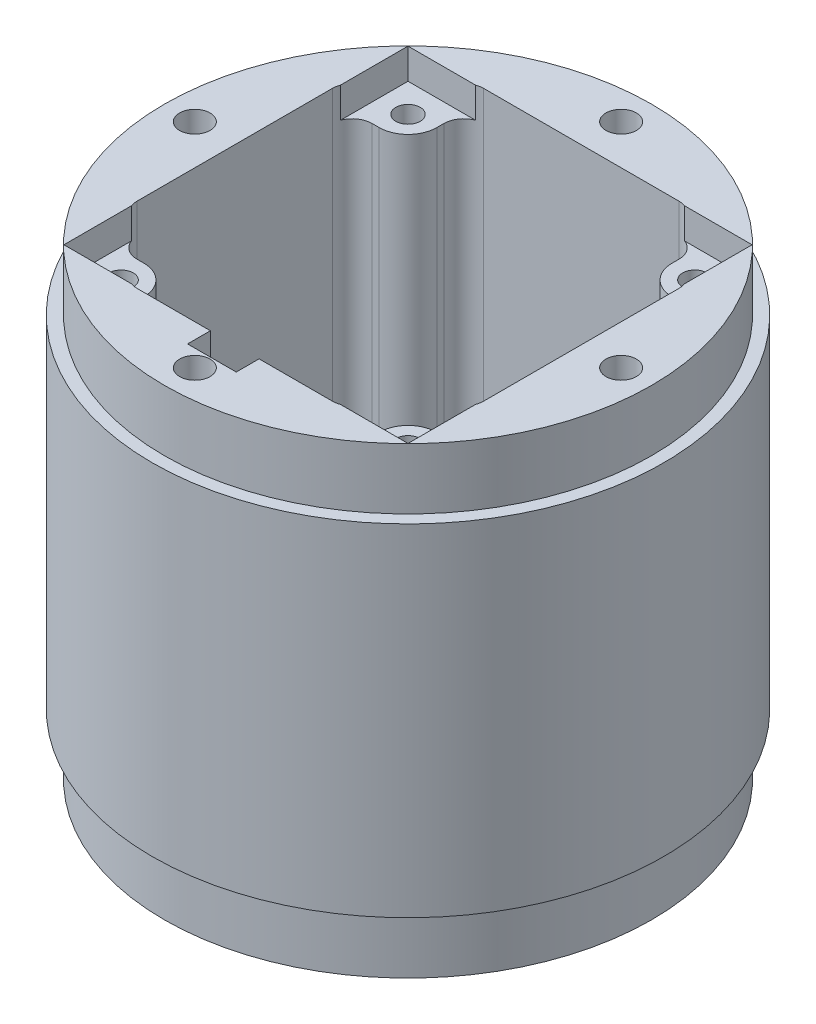
SolidWorks part; units mm, degrees
ref_plane "Front Plane" through (0, 0, 0) normal (0, 0, 1) x (1, 0, 0)
ref_plane "Top Plane" through (0, 0, 0) normal (0, 1, 0) x (1, 0, 0)
ref_plane "Right Plane" through (0, 0, 0) normal (1, 0, 0) x (0, 0, -1)
sketch "Sketch2" plane through (0, 0, 0) normal (0, 1, 0) x (1, 0, 0)
  line L0 (-16.05, 28.45) -> (16.05, 28.45)
  line L5 (19.3, 25.2) -> (19.3, 24.05)
  line L7 (-16.05, 28.2) -> (16.05, 28.2) construction
  line L8 (-28.2, 16.05) -> (-28.2, -16.05)
  line L9 (-16.05, -28.2) -> (16.05, -28.2)
  line L10 (28.2, 16.05) -> (28.2, -16.05)
  line L11 (25.2, 19.3) -> (24.05, 19.3)
  line L12 (28.45, 16.05) -> (28.45, -16.05)
  line L15 (-25.2, 19.05) -> (-24.05, 19.05)
  line L16 (-19.05, 25.2) -> (-19.05, 24.05)
  line L19 (25.2, 19.05) -> (24.05, 19.05)
  line L20 (19.05, 25.2) -> (19.05, 24.05)
  line L21 (-24.05, -19.05) -> (-25.2, -19.05)
  line L22 (-19.05, -24.05) -> (-19.05, -25.2)
  line L25 (24.05, -19.05) -> (25.2, -19.05)
  line L26 (19.05, -24.05) -> (19.05, -25.2)
  line L27 (24.05, -19.3) -> (25.2, -19.3)
  line L28 (19.3, -24.05) -> (19.3, -25.2)
  line L29 (-16.05, -28.45) -> (16.05, -28.45)
  line L30 (-19.3, -24.05) -> (-19.3, -25.2)
  line L31 (-24.05, -19.3) -> (-25.2, -19.3)
  line L32 (-28.45, 16.05) -> (-28.45, -16.05)
  line L33 (-25.2, 19.3) -> (-24.05, 19.3)
  line L34 (-19.3, 25.2) -> (-19.3, 24.05)
  circle A0 centre (0, 0) radius 40
  arc A1 (24.05, 19.05) -> (19.05, 24.05) centre (24.05, 24.05) cw
  arc A2 (-24.05, 19.05) -> (-19.05, 24.05) centre (-24.05, 24.05) ccw
  arc A3 (-24.05, -19.05) -> (-19.05, -24.05) centre (-24.05, -24.05) cw
  arc A4 (19.05, -24.05) -> (24.05, -19.05) centre (24.05, -24.05) cw
  arc A5 (-28.2, 16.05) -> (-25.2, 19.05) centre (-25.2, 16.05) cw
  arc A6 (-28.2, -16.05) -> (-25.2, -19.05) centre (-25.2, -16.05) ccw
  arc A7 (-16.05, -28.2) -> (-19.05, -25.2) centre (-16.05, -25.2) cw
  arc A8 (16.05, -28.2) -> (19.05, -25.2) centre (16.05, -25.2) ccw
  arc A9 (25.2, -19.05) -> (28.2, -16.05) centre (25.2, -16.05) ccw
  arc A10 (28.2, 16.05) -> (25.2, 19.05) centre (25.2, 16.05) ccw
  arc A11 (16.05, 28.2) -> (19.05, 25.2) centre (16.05, 25.2) cw
  arc A12 (-19.05, 25.2) -> (-16.05, 28.2) centre (-16.05, 25.2) cw
  arc A13 (16.05, 28.45) -> (19.3, 25.2) centre (16.05, 25.2) cw
  arc A14 (24.05, 19.3) -> (19.3, 24.05) centre (24.05, 24.05) cw
  arc A15 (28.45, 16.05) -> (25.2, 19.3) centre (25.2, 16.05) ccw
  arc A16 (25.2, -19.3) -> (28.45, -16.05) centre (25.2, -16.05) ccw
  arc A17 (19.3, -24.05) -> (24.05, -19.3) centre (24.05, -24.05) cw
  arc A18 (16.05, -28.45) -> (19.3, -25.2) centre (16.05, -25.2) ccw
  arc A19 (-16.05, -28.45) -> (-19.3, -25.2) centre (-16.05, -25.2) cw
  arc A20 (-24.05, -19.3) -> (-19.3, -24.05) centre (-24.05, -24.05) cw
  arc A21 (-28.45, -16.05) -> (-25.2, -19.3) centre (-25.2, -16.05) ccw
  arc A22 (-28.45, 16.05) -> (-25.2, 19.3) centre (-25.2, 16.05) cw
  arc A23 (-24.05, 19.3) -> (-19.3, 24.05) centre (-24.05, 24.05) ccw
  arc A24 (-19.3, 25.2) -> (-16.05, 28.45) centre (-16.05, 25.2) cw
  point P0 (0, 0)
  point P6 (0, 0)
  point P11 (19.05, 19.05)
  point P24 (-19.05, -19.05)
  point P27 (19.05, -19.05)
  point P40 (28.2, 19.05)
  point P43 (19.05, 28.2)
  point P46 (-19.05, 28.2)
  dimension "D7" = 80
  dimension "D8" = 5
  dimension "D9" = 3
  dimension "D1" = 38.1
  dimension "D2" = 38.1
  dimension "D3" = 9.15
  dimension "D4" = 38.1
  dimension "D5" = 9.15
  dimension "D6" = 28.2
  dimension "D10" = 0.25
extrude "Boss-Extrude1" add sketch "Sketch2" along normal blind 76 contours A0 L34 A24 L0 A13 L5 A14 L11 A15 L12 A16 L27 A17 L28 A18 L29 A19 L30 A20 L31 A21 L32 A22 L33 A23
sketch "Sketch3" plane through (0, 0, 28.2) normal (0, 0, -1) x (-1, 0, 0)
  line L0 (16.05, 0) -> (-16.05, 0) construction
  line L1 (-4, 76) -> (4, 76)
  line L2 (-4, 76) -> (-4, 0)
  line L3 (-4, 0) -> (4, 0)
  line L4 (4, 76) -> (4, 0)
  point P6 (0, 0)
  dimension "D1" = 8
  dimension "D2" = 76
extrude "Cut-Extrude1" cut sketch "Sketch3" against normal blind 4
ref_plane "Plane1" through (0, 38, 0) normal (0, 1, 0) x (1, 0, 0)
sketch "Sketch4" plane through (0, 38, 0) normal (0, 1, 0) x (1, 0, 0)
  circle A0 centre (0, 0) radius 42
  circle A1 centre (0, 0) radius 40
  dimension "D1" = 84
extrude "Boss-Extrude3" add sketch "Sketch4" along normal mid plane 56
sketch "Sketch5" plane through (0, 76, 0) normal (0, 1, 0) x (1, 0, 0)
  line L1 (-28.25, 28.25) -> (28.25, 28.25)
  line L2 (-28.25, 28.25) -> (-28.25, -28.25)
  line L3 (-28.25, -28.25) -> (28.25, -28.25)
  line L4 (28.25, 28.25) -> (28.25, -28.25)
  line L5 (-28.25, 28.25) -> (28.25, -28.25) construction
  line L6 (-28.25, -28.25) -> (28.25, 28.25) construction
  point P0 (0, 0)
  dimension "D1" = 56.5
extrude "Cut-Extrude7" cut sketch "Sketch5" against normal blind 5
sketch "Sketch6" plane through (0, 71, 0) normal (0, 1, 0) x (1, 0, 0)
  line L1 (-23.55, 23.55) -> (23.55, 23.55)
  line L2 (-23.55, 23.55) -> (-23.55, -23.55)
  line L3 (-23.55, -23.55) -> (23.55, -23.55)
  line L4 (23.55, 23.55) -> (23.55, -23.55)
  line L5 (-23.55, 23.55) -> (23.55, -23.55) construction
  line L6 (-23.55, -23.55) -> (23.55, 23.55) construction
  circle A0 centre (-23.55, 23.55) radius 2
  circle A1 centre (23.55, 23.55) radius 2
  circle A2 centre (23.55, -23.55) radius 2
  circle A3 centre (-23.55, -23.55) radius 2
  point P0 (0, 0)
  dimension "D3" = 4
  dimension "D1" = 47.1
  dimension "D2" = 47.1
extrude "Cut-Extrude8" cut sketch "Sketch6" against normal through all contours A0 | A1 | A3 | A2
sketch "Sketch7" plane through (0, 76, 0) normal (0, 1, 0) x (1, 0, 0)
  circle A0 centre (0, 0) radius 35
  circle A1 centre (0, 35) radius 2.5
  circle A2 centre (35, 0) radius 2.5
  circle A3 centre (0, -35) radius 2.5
  circle A4 centre (-35, 0) radius 2.5
  point P14 (0, 0)
  dimension "D1" = 70
  dimension "D2" = 5
  dimension "D3" = 4
extrude "Cut-Extrude9" cut sketch "Sketch7" against normal through all contours A4 | A1 | A2 | A3
